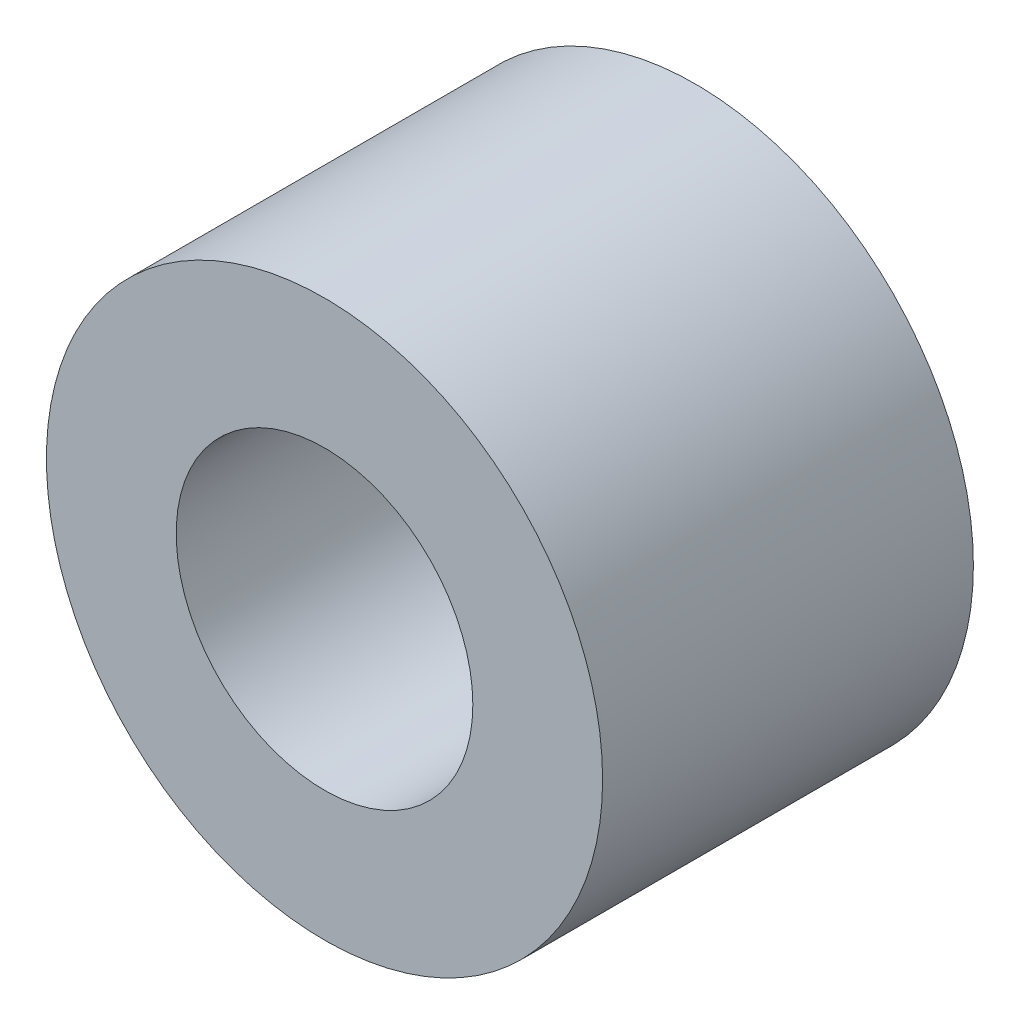
SolidWorks part; units mm, degrees
ref_plane "前视基准面" through (0, 0, 0) normal (0, 0, 1) x (1, 0, 0)
ref_plane "上视基准面" through (0, 0, 0) normal (0, 1, 0) x (1, 0, 0)
ref_plane "右视基准面" through (0, 0, 0) normal (1, 0, 0) x (0, 0, -1)
other "Configuration Table"
sketch "草图1" plane through (0, 0, 0) normal (0, 0, 1) x (1, 0, 0)
  circle A0 centre (0, 0) radius 3
  circle A1 centre (0, 0) radius 1.6
extrude "凸台-拉伸1" add sketch "草图1" along normal mid plane 4
